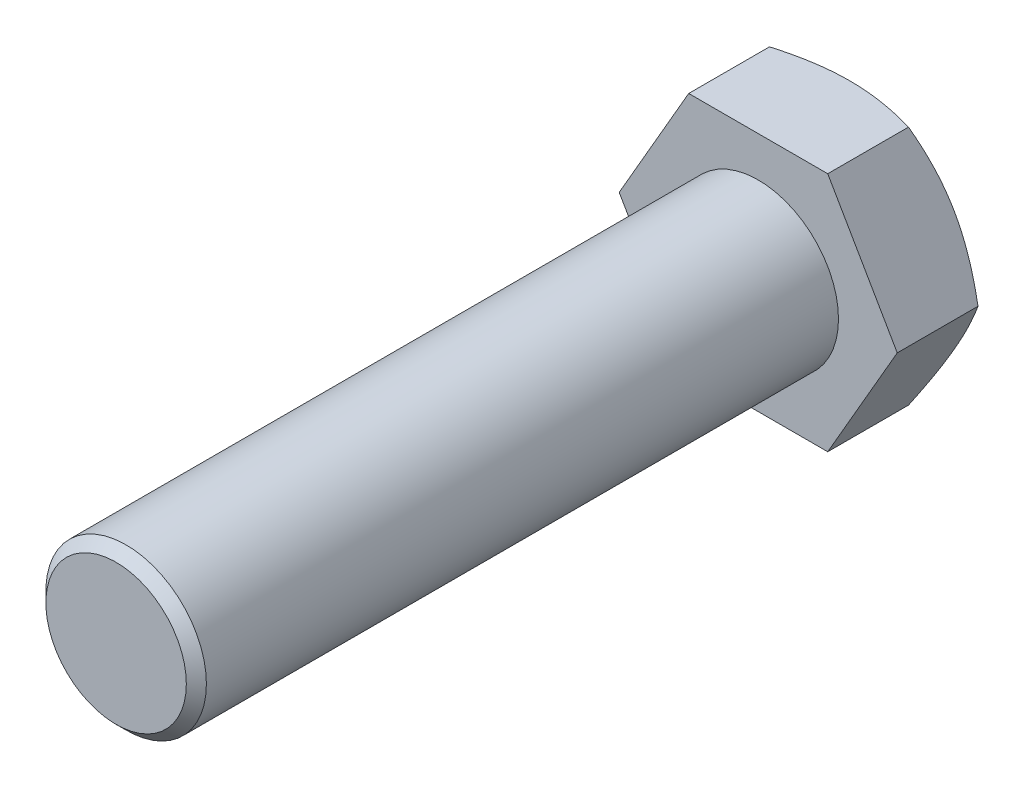
SolidWorks part; units mm, degrees
ref_plane "Front Plane" through (0, 0, 0) normal (0, 0, 1) x (1, 0, 0)
ref_plane "Top Plane" through (0, 0, 0) normal (0, 1, 0) x (1, 0, 0)
ref_plane "Right Plane" through (0, 0, 0) normal (1, 0, 0) x (0, 0, -1)
ref_axis "Central Axis" through (0, 0, -10.1409) along (0, 0, 1)
sketch "Head Sketch" plane through (0, 0, 0) normal (0, 0, 1) x (1, 0, 0)
  line L1 (10.9985, 0) -> (5.4993, 9.525)
  line L2 (5.4993, 9.525) -> (-5.4993, 9.525)
  line L3 (-5.4993, 9.525) -> (-10.9985, 0)
  line L4 (-10.9985, 0) -> (-5.4993, -9.525)
  line L5 (-5.4993, -9.525) -> (5.4993, -9.525)
  line L6 (5.4993, -9.525) -> (10.9985, 0)
  circle A0 centre (0, 0) radius 9.525 construction
  dimension "D1" = 19.05
extrude "Head" add sketch "Head Sketch" against normal blind 7.239 contours L2 L3 L4 L5 L6 L1
sketch "Head Chamfer Ref Sketch" plane through (0, 0, -7.239) normal (0, 0, -1) x (-1, 0, 0)
  line L0 (-10.9985, 0) -> (-5.4993, 9.525) construction
  line L1 (0, 0) -> (-10.9985, 0)
  circle A0 centre (0, 0) radius 9.525
  point P5 (-9.525, 0)
sketch "Sketch9" plane through (0, 0, 0) normal (0, 1, 0) x (1, 0, 0)
  line L0 (10.9985, 7.239) -> (9.525, 7.239)
  line L1 (9.525, 7.239) -> (10.9985, 6.3883)
  line L2 (10.9985, 6.3883) -> (10.9985, 7.239)
  line L3 (10.9985, 7.239) -> (10.9985, 0) construction
  dimension "D1" = 30
revolve "Head Chamfer" cut sketch "Sketch9" angle 360 about axis through (0, 0, -10.1409) along (0, 0, 1)
sketch "Sketch2" plane through (0, 0, 0) normal (0, 0, 1) x (1, 0, 0)
  circle A0 centre (0, 0) radius 6.35
  dimension "D1" = 12.7
extrude "Shaft" add sketch "Sketch2" along normal blind 50.8
chamfer "Shaft Chamfer" distance 0.7937 angle 45 1 edges at (6.35, 0, 50.8)
